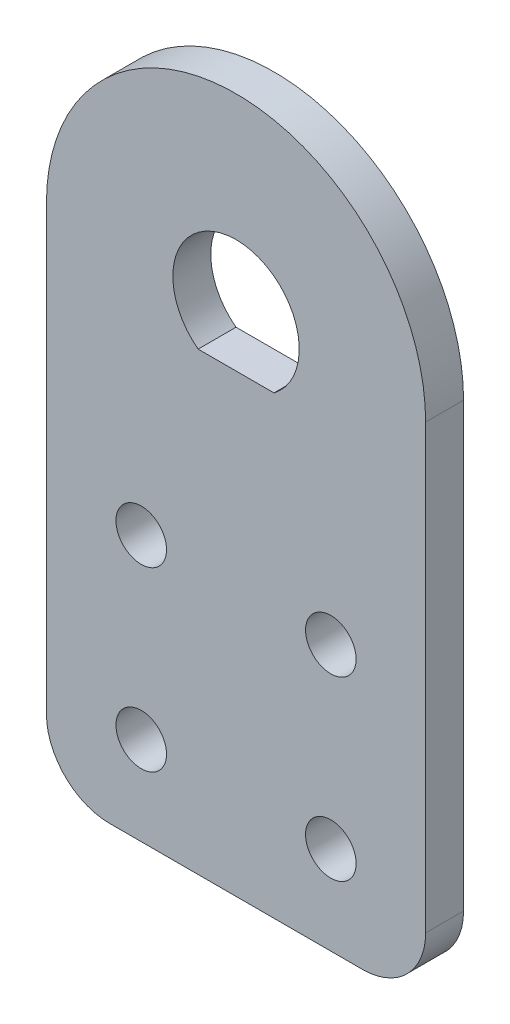
SolidWorks part; units mm, degrees
material "Thornel Mat VMA"
ref_plane "前视基准面" through (0, 0, 0) normal (0, 0, 1) x (1, 0, 0)
ref_plane "上视基准面" through (0, 0, 0) normal (0, 1, 0) x (1, 0, 0)
ref_plane "右视基准面" through (0, 0, 0) normal (1, 0, 0) x (0, 0, -1)
sketch "草图1" plane through (0, 0, 0) normal (0, 0, 1) x (1, 0, 0)
  line L0 (-15, 9.3668) -> (-15, -30.6332)
  line L1 (-15, -30.6332) -> (15, -30.6332)
  line L2 (15, -30.6332) -> (15, 9.3668)
  line L9 (3, 5.3668) -> (-3, 5.3668)
  circle A3 centre (-7.5, -9.6332) radius 2
  circle A4 centre (-7.5, -23.6332) radius 2
  circle A5 centre (7.5, -23.6332) radius 2
  circle A6 centre (7.5, -9.6332) radius 2
  arc A8 (15, 9.3668) -> (-15, 9.3668) centre (0, 9.3668) ccw
  arc A9 (3, 5.3668) -> (-3, 5.3668) centre (0, 9.3668) ccw
  dimension "D1" = 4
  dimension "D2" = 7
  dimension "D3" = 14
extrude "凸台-拉伸1" add sketch "草图1" along normal blind 3
fillet "圆角1" radius 5 2 edges at (15, -30.6332, 1.5) (-15, -30.6332, 1.5)
